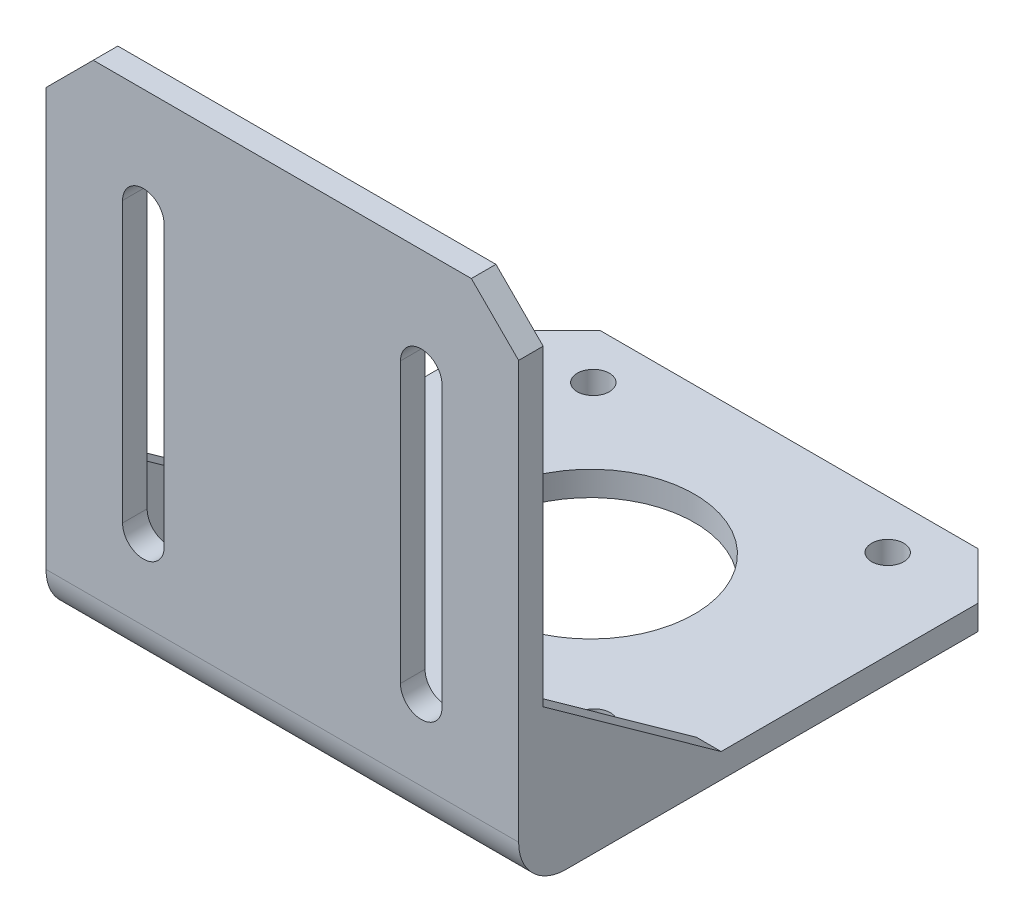
SolidWorks part; units mm, degrees
ref_plane "Alzado" through (0, 0, 0) normal (0, 0, 1) x (1, 0, 0)
ref_plane "Planta" through (0, 0, 0) normal (0, 1, 0) x (1, 0, 0)
ref_plane "Vista lateral" through (0, 0, 0) normal (1, 0, 0) x (0, 0, -1)
sketch "Croquis3" plane through (0, 0, 0) normal (0, 0, 1) x (1, 0, 0)
  line L0 (14.7, 15.775) -> (14.7, -13.775) construction
  line L1 (-25, -27.075) -> (25, -27.075)
  line L2 (-25, -27.075) -> (-25, 22.075)
  line L3 (-20, 27.075) -> (20, 27.075)
  line L4 (25, -27.075) -> (25, 22.075)
  line L5 (-25, -27.075) -> (25, 27.075) construction
  line L6 (-25, 27.075) -> (25, -27.075) construction
  line L7 (16.9, 15.775) -> (16.9, -13.775)
  line L8 (12.5, 15.775) -> (12.5, -13.775)
  line L9 (0, 0) -> (27.0857, 0) construction
  line L10 (0, 0) -> (0, 13.9552) construction
  line L11 (-14.7, 15.775) -> (-14.7, -13.775) construction
  line L12 (-16.9, 15.775) -> (-16.9, -13.775)
  line L13 (-12.5, 15.775) -> (-12.5, -13.775)
  line L14 (-25, 22.075) -> (-20, 27.075)
  line L15 (20, 27.075) -> (25, 22.075)
  arc A0 (16.9, 15.775) -> (12.5, 15.775) centre (14.7, 15.775) ccw
  arc A1 (12.5, -13.775) -> (16.9, -13.775) centre (14.7, -13.775) ccw
  arc A2 (-16.9, 15.775) -> (-12.5, 15.775) centre (-14.7, 15.775) cw
  arc A3 (-12.5, -13.775) -> (-16.9, -13.775) centre (-14.7, -13.775) cw
  point P0 (0, 0)
  point P8 (14.7, 1)
  point P13 (14.7, 17.975)
  point P14 (14.7, -15.975)
  point P19 (-14.7, 1)
  dimension "D1" = 50
  dimension "D2" = 54.15
  dimension "D3" = 33.95
  dimension "D4" = 8.1
  dimension "D5" = 9.1
  dimension "D6" = 4.4
extrude "Saliente-Extruir1" add sketch "Croquis3" along normal blind 2.6
sketch "Croquis5" plane through (0, 0, 0) normal (0, 0, -1) x (-1, 0, 0)
  line L0 (-25, -27.075) -> (-25, 22.075) construction
  line L1 (-25, -24.475) -> (25, -24.475)
  line L2 (-25, -24.475) -> (-25, -27.075)
  line L3 (-25, -27.075) -> (25, -27.075)
  line L4 (25, -24.475) -> (25, -27.075)
  dimension "D1" = 2.6
extrude "Saliente-Extruir2" add sketch "Croquis5" along normal blind 51
fillet "Redondeo1" radius 5 1 edges at (0, -27.075, 2.6)
sketch "Croquis7" plane through (0, -24.475, 0) normal (0, 1, 0) x (1, 0, 0)
  line L1 (-25, 51) -> (25, 51) construction
  line L2 (0, 0) -> (0, 60) construction
  line L8 (-14.3729, 44.6729) -> (7.6974, 22.1419) construction
  line L11 (-8.1815, 22.6473) -> (7.8089, 37.7473) construction
  circle A0 centre (0, 30) radius 11
  circle A1 centre (-15.575, 45.875) radius 1.7
  circle A2 centre (15.575, 45.875) radius 1.7
  circle A3 centre (15.575, 14.825) radius 1.7
  circle A4 centre (-15.575, 14.725) radius 1.7
  dimension "D1" = 22
  dimension "D2" = 10
  dimension "D3" = 3.4
  dimension "D4" = 3.4
  dimension "D5" = 3.4
  dimension "D6" = 3.4
  dimension "D7" = 31.15
  dimension "D8" = 31.15
extrude "Cortar-Extruir1" cut sketch "Croquis7" against normal through all
chamfer "Chaflán1" distance 5 angle 45 2 edges at (-25, -25.775, -51) (25, -25.775, -51)
sketch "Croquis8" plane through (0, -24.475, 0) normal (0, 1, 0) x (1, 0, 0)
  line L0 (-25, 0) -> (-25, 20)
  line L1 (-25, 46) -> (-25, 0) construction
  line L2 (-25, 20) -> (-22.4, 20)
  line L3 (-22.4, 20) -> (-22.4, 0)
  line L4 (25, 0) -> (-25, 0) construction
  line L5 (-22.4, 0) -> (-25, 0)
  line L6 (0, 0) -> (0, 12.59) construction
  line L7 (20, 0) -> (-20, 0) construction
  line L8 (22.4, 0) -> (25, 0)
  line L9 (22.4, 20) -> (22.4, 0)
  line L10 (25, 0) -> (25, 20)
  line L11 (25, 20) -> (22.4, 20)
  dimension "D1" = 2.6
  dimension "D2" = 20
extrude "Saliente-Extruir3" add sketch "Croquis8" along normal blind 14.5
sketch "Croquis9" plane through (-25, 0, 0) normal (-1, 0, 0) x (0, 0, 1)
  line L3 (-20, -24.475) -> (-18.8272, -24.475)
  line L4 (-18.8272, -24.475) -> (0, -10.9658)
  line L5 (0, -10.9658) -> (0, -9.975)
  line L6 (-20, -24.475) -> (-20, -9.975)
  line L7 (-20, -9.975) -> (-20, -24.475) construction
  line L8 (-20, -9.975) -> (0, -9.975)
  dimension "D1" = 23.1724
extrude "Cortar-Extruir2" cut sketch "Croquis9" against normal through all
fillet "Redondeo2" radius 2.6 1 edges at (0, -24.475, 0)
